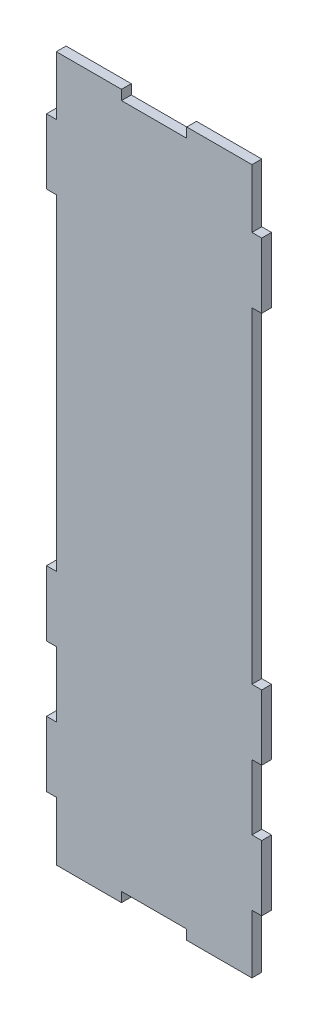
SolidWorks part; units mm, degrees
ref_plane "Front Plane" through (0, 0, 0) normal (0, 0, 1) x (1, 0, 0)
ref_plane "Top Plane" through (0, 0, 0) normal (0, 1, 0) x (1, 0, 0)
ref_plane "Right Plane" through (0, 0, 0) normal (1, 0, 0) x (0, 0, -1)
sketch "Sketch1" plane through (0, 0, 0) normal (0, 0, 1) x (1, 0, 0)
  line L0 (0, 0) -> (0, 100)
  line L1 (0, 100) -> (-3, 100)
  line L2 (-3, 100) -> (-3, 120)
  line L3 (-3, 120) -> (0, 120)
  line L4 (0, 120) -> (0, 138)
  line L5 (0, 138) -> (20, 138)
  line L6 (20, 138) -> (20, 135)
  line L7 (20, 135) -> (40, 135)
  line L8 (40, 135) -> (40, 138)
  line L9 (40, 138) -> (60, 138)
  line L10 (60, 138) -> (60, 120)
  line L11 (63, 120) -> (60, 120)
  line L12 (63, 120) -> (63, 100)
  line L13 (63, 100) -> (60, 100)
  line L14 (60, 100) -> (60, 0)
  line L15 (60, 0) -> (63, 0)
  line L16 (63, 0) -> (63, -20)
  line L17 (63, -20) -> (60, -20)
  line L18 (60, -20) -> (60, -40)
  line L19 (60, -40) -> (63, -40)
  line L20 (63, -40) -> (63, -60)
  line L21 (63, -60) -> (60, -60)
  line L22 (60, -60) -> (60, -78)
  line L23 (60, -78) -> (40, -78)
  line L24 (0, -78) -> (0, -60)
  line L25 (0, -60) -> (-3, -60)
  line L26 (-3, -60) -> (-3, -40)
  line L27 (-3, -40) -> (0, -40)
  line L28 (0, -40) -> (0, -20)
  line L29 (0, -20) -> (-3, -20)
  line L30 (-3, -20) -> (-3, 0)
  line L31 (-3, 0) -> (0, 0)
  line L32 (20, -78) -> (20, -75)
  line L33 (20, -75) -> (40, -75)
  line L34 (40, -75) -> (40, -78)
  line L35 (20, -78) -> (0, -78)
  dimension "D1" = 18
  dimension "D2" = 18
  dimension "D3" = 18
  dimension "D4" = 18
  dimension "D5" = 3
  dimension "D6" = 216
  dimension "D7" = 60
extrude "Boss-Extrude1" add sketch "Sketch1" along normal blind 3
